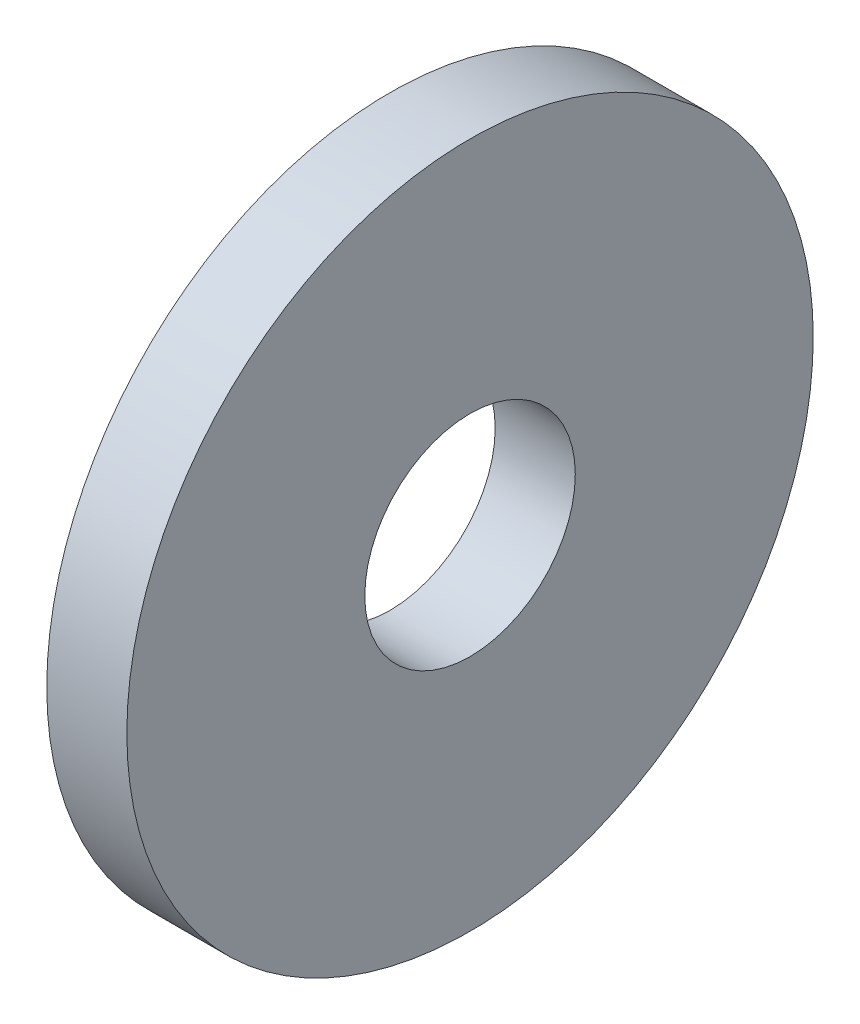
SolidWorks part; units mm, degrees
ref_plane "Plane1" through (0, 0, 0) normal (0, 0, 1) x (1, 0, 0)
ref_plane "Plane2" through (0, 0, 0) normal (0, 1, 0) x (1, 0, 0)
ref_plane "Plane3" through (0, 0, 0) normal (1, 0, 0) x (0, 0, -1)
sketch "Sketch1" plane through (0, 0, 0) normal (0, 0, 1) x (1, 0, 0)
  line L0 (-34.925, 0) -> (9.525, 0) construction
  line L1 (0, 1.84) -> (0, 6)
  line L2 (0, 6) -> (-1.4, 6)
  line L3 (-1.4, 6) -> (-1.4, 1.84)
  line L4 (-1.4, 1.84) -> (0, 1.84)
  dimension "Thickness" = 1.4
  dimension "Inside_dia" = 3.68
  dimension "Outside_dia" = 12
revolve "Base-Revolve" add sketch "Sketch1" angle 360 about L0
